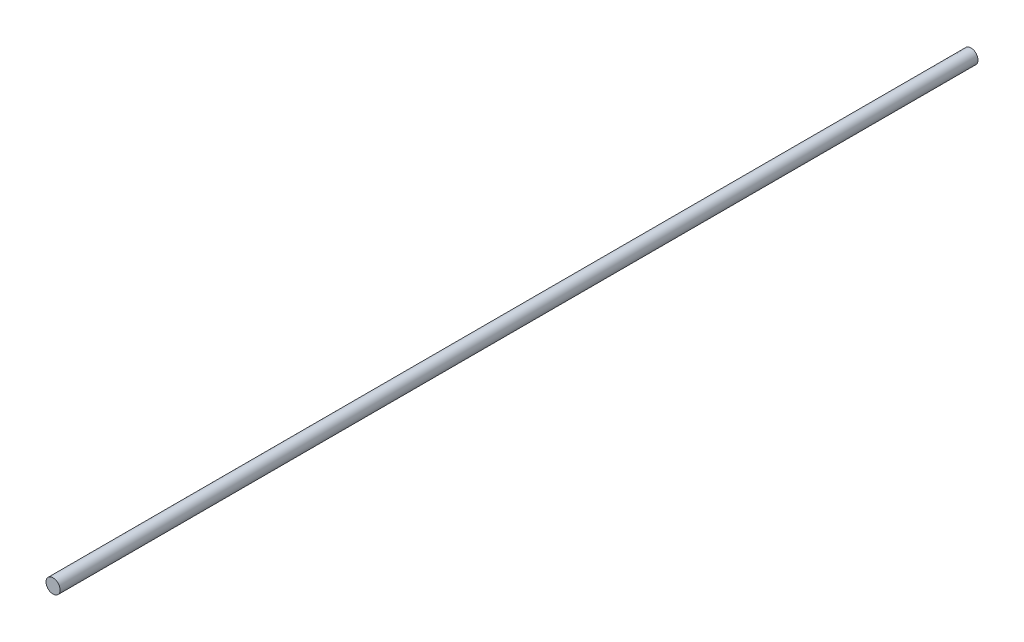
SolidWorks part; units mm, degrees
material "1.4000 (X6Cr13)"
ref_plane "Ebene vorne" through (0, 0, 0) normal (0, 0, 1) x (1, 0, 0)
ref_plane "Ebene oben" through (0, 0, 0) normal (0, 1, 0) x (1, 0, 0)
ref_plane "Ebene rechts" through (0, 0, 0) normal (1, 0, 0) x (0, 0, -1)
sketch "Skizze1" plane through (0, 0, 0) normal (0, 0, 1) x (1, 0, 0)
  circle A0 centre (0, 0) radius 4
extrude "Aufsatz-Linear austragen1" add sketch "Skizze1" along normal blind 520
